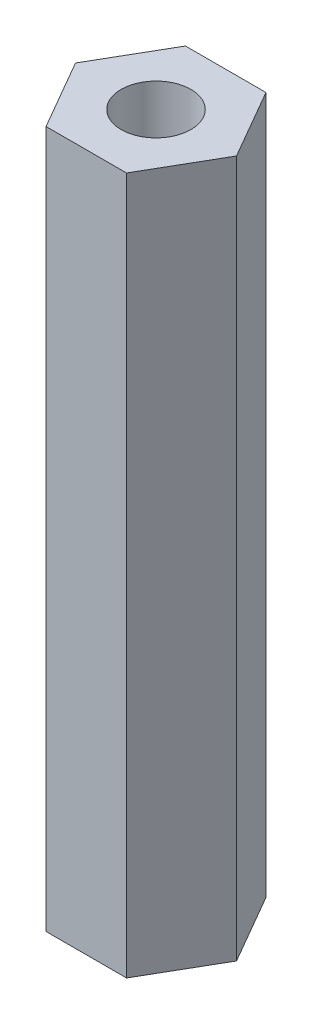
SolidWorks part; units mm, degrees
ref_plane "前视基准面" through (0, 0, 0) normal (0, 0, 1) x (1, 0, 0)
ref_plane "上视基准面" through (0, 0, 0) normal (0, 1, 0) x (1, 0, 0)
ref_plane "右视基准面" through (0, 0, 0) normal (1, 0, 0) x (0, 0, -1)
sketch "草图1" plane through (0, 0, 0) normal (0, 1, 0) x (1, 0, 0)
  line L1 (2.3094, 0) -> (1.1547, 2)
  line L2 (1.1547, 2) -> (-1.1547, 2)
  line L3 (-1.1547, 2) -> (-2.3094, 0)
  line L4 (-2.3094, 0) -> (-1.1547, -2)
  line L5 (-1.1547, -2) -> (1.1547, -2)
  line L6 (1.1547, -2) -> (2.3094, 0)
  circle A0 centre (0, 0) radius 2 construction
  circle A1 centre (0, 0) radius 1
  dimension "D2" = 2
  dimension "D1" = 4
extrude "凸台-拉伸1" add sketch "草图1" along normal mid plane 20
